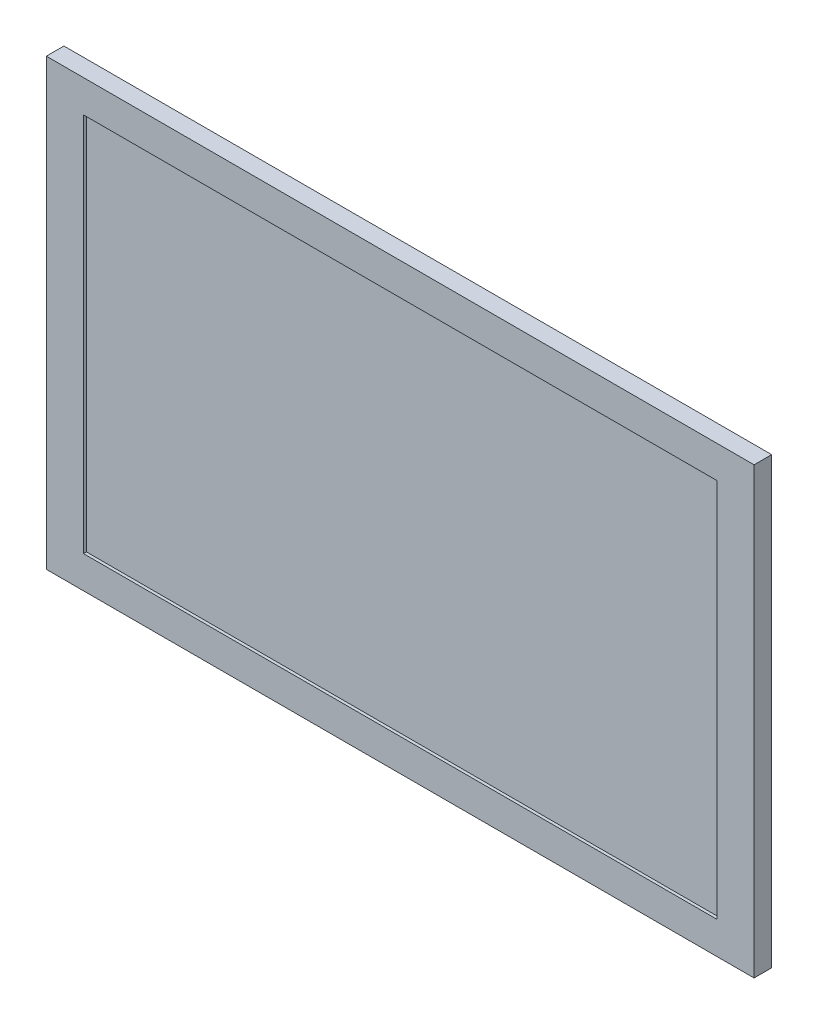
SolidWorks part; units mm, degrees
ref_plane "Front Plane" through (0, 0, 0) normal (0, 0, 1) x (1, 0, 0)
ref_plane "Top Plane" through (0, 0, 0) normal (0, 1, 0) x (1, 0, 0)
ref_plane "Right Plane" through (0, 0, 0) normal (1, 0, 0) x (0, 0, -1)
sketch "Sketch1" plane through (0, 0, 0) normal (0, 0, 1) x (1, 0, 0)
  line L1 (-60.35, 37.9) -> (60.35, 37.9)
  line L2 (-60.35, 37.9) -> (-60.35, -37.9)
  line L3 (-60.35, -37.9) -> (60.35, -37.9)
  line L4 (60.35, 37.9) -> (60.35, -37.9)
  line L5 (-60.35, 37.9) -> (60.35, -37.9) construction
  line L6 (-60.35, -37.9) -> (60.35, 37.9) construction
  point P0 (0, 0)
  dimension "D1" = 120.7
  dimension "D2" = 75.8
extrude "Boss-Extrude1" add sketch "Sketch1" along normal mid plane 3
sketch "Sketch2" plane through (0, 0, 1.5) normal (0, 0, 1) x (1, 0, 0)
  line L1 (-54, 32.4) -> (54, 32.4)
  line L2 (-54, 32.4) -> (-54, -32.4)
  line L3 (-54, -32.4) -> (54, -32.4)
  line L4 (54, 32.4) -> (54, -32.4)
  line L5 (-54, 32.4) -> (54, -32.4) construction
  line L6 (-54, -32.4) -> (54, 32.4) construction
  point P0 (0, 0)
  point P6 (0, 0)
  dimension "D1" = 108
  dimension "D2" = 64.8
extrude "Cut-Extrude1" cut sketch "Sketch2" against normal blind 0.5
